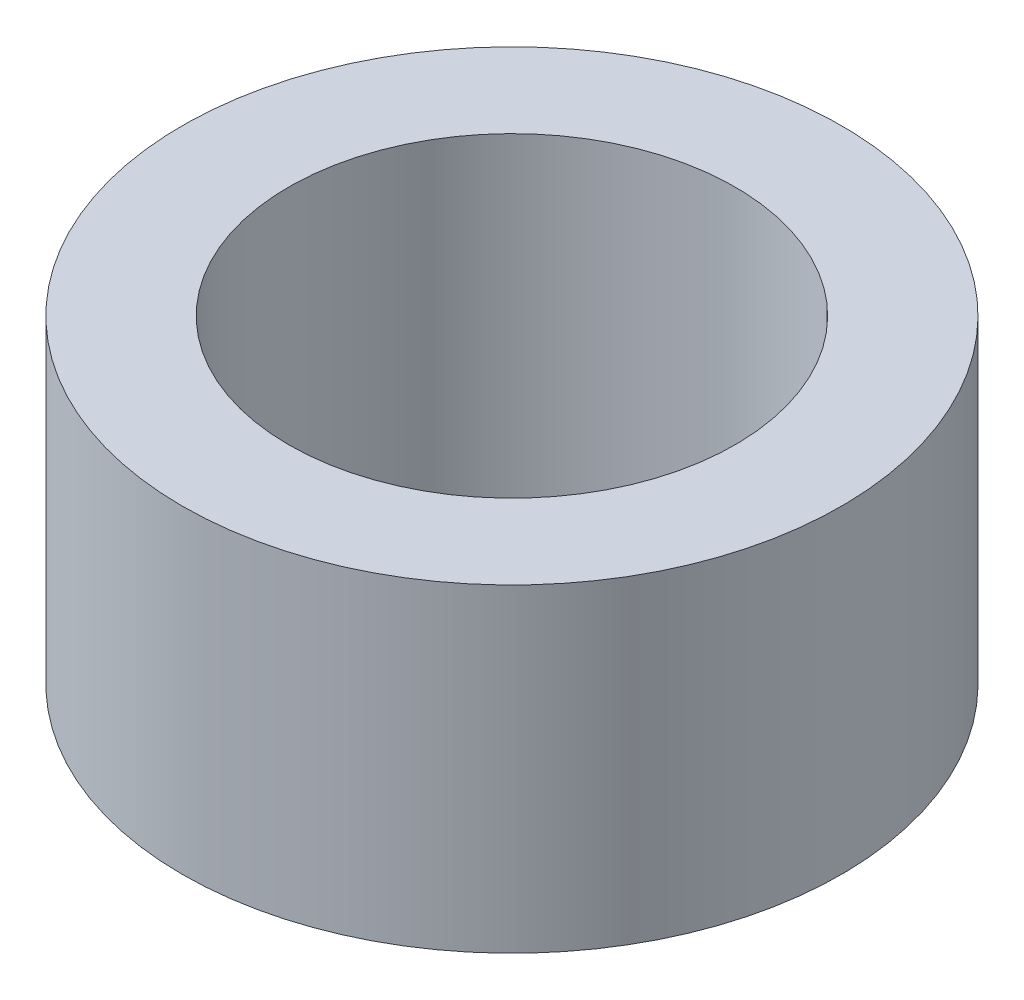
SolidWorks part; units mm, degrees
ref_plane "Front Plane" through (0, 0, 0) normal (0, 0, 1) x (1, 0, 0)
ref_plane "Top Plane" through (0, 0, 0) normal (0, 1, 0) x (1, 0, 0)
ref_plane "Right Plane" through (0, 0, 0) normal (1, 0, 0) x (0, 0, -1)
sketch "Sketch1" plane through (0, 0, 0) normal (0, 1, 0) x (1, 0, 0)
  circle A0 centre (0, 0) radius 3.1
  circle A1 centre (0, 0) radius 2.1
  dimension "D1" = 6.2
  dimension "D2" = 4.2
extrude "Boss-Extrude1" add sketch "Sketch1" along normal blind 3
